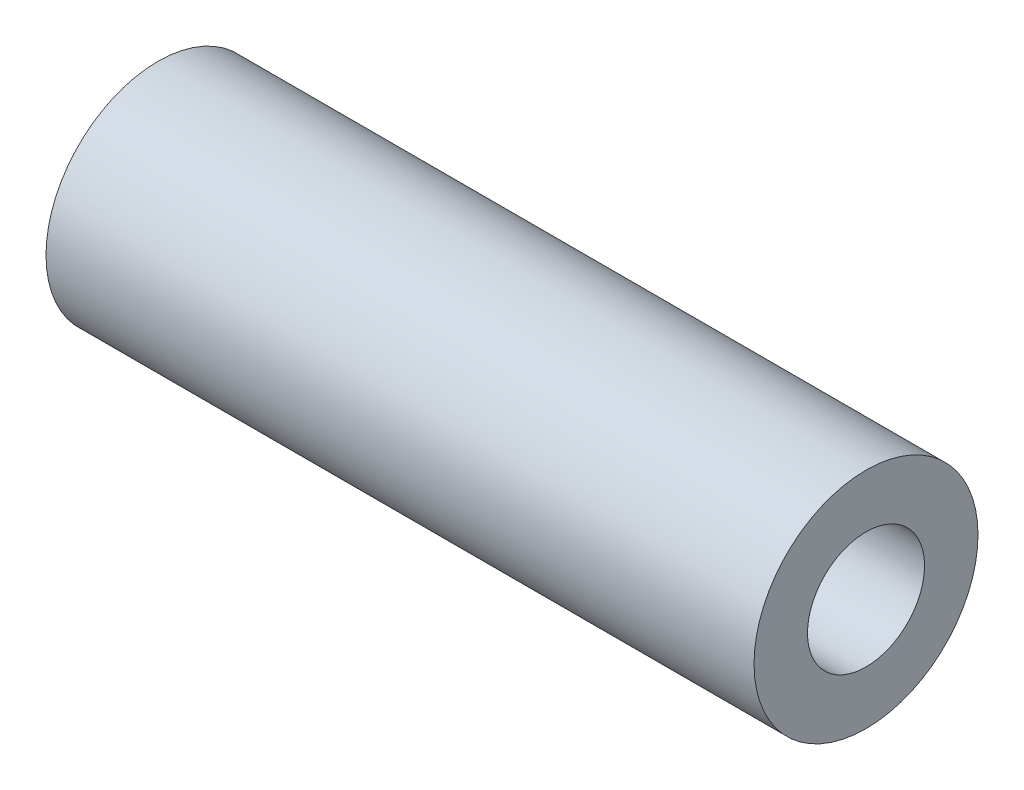
SolidWorks part; units mm, degrees
material "6061-T6 (SS)"
ref_plane "Front Plane" through (0, 0, 0) normal (0, 0, 1) x (1, 0, 0)
ref_plane "Top Plane" through (0, 0, 0) normal (0, 1, 0) x (1, 0, 0)
ref_plane "Right Plane" through (0, 0, 0) normal (1, 0, 0) x (0, 0, -1)
sketch "Sketch1" plane through (0, 0, 0) normal (1, 0, 0) x (0, 0, -1)
  circle A0 centre (0, 0) radius 4.7625
  circle A1 centre (0, 0) radius 2.4892
  dimension "D1" = 4.9784
  dimension "D2" = 9.525
extrude "Boss-Extrude1" add sketch "Sketch1" along normal mid plane 30.1117
